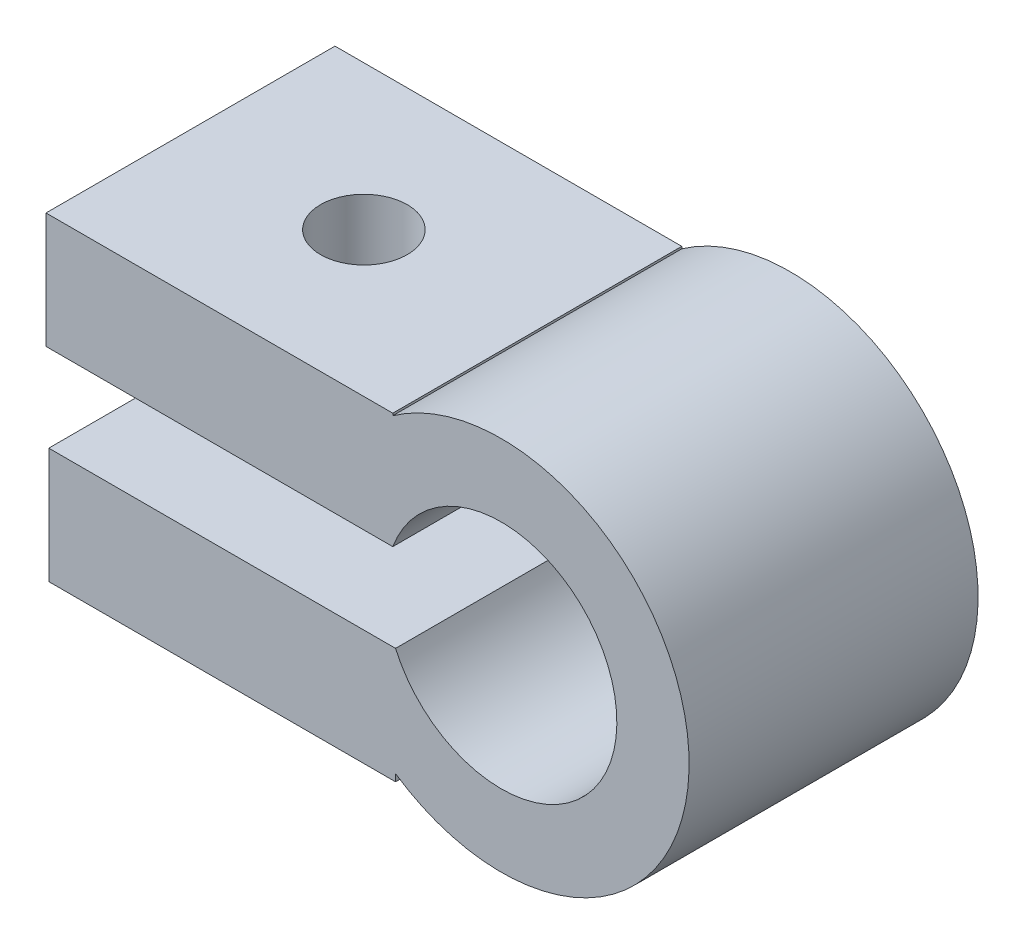
SolidWorks part; units mm, degrees
ref_plane "Front Plane" through (0, 0, 0) normal (0, 0, 1) x (1, 0, 0)
ref_plane "Top Plane" through (0, 0, 0) normal (0, 1, 0) x (1, 0, 0)
ref_plane "Right Plane" through (0, 0, 0) normal (1, 0, 0) x (0, 0, -1)
sketch "Sketch1" plane through (0, 0, 0) normal (0, 0, 1) x (1, 0, 0)
  circle A0 centre (-12.3154, 2.5507) radius 4
  circle A1 centre (-12.3154, 2.5507) radius 6.5
  dimension "D1" = 8
  dimension "D2" = 13
extrude "Boss-Extrude1" add sketch "Sketch1" along normal blind 10 contours A1
sketch "Sketch2" plane through (0, 0, 10) normal (0, 0, 1) x (1, 0, 0)
  line L1 (-18.9664, 3.9327) -> (-15.7482, 3.9327)
  line L2 (-18.9664, 3.9327) -> (-18.9664, 0.9327)
  line L3 (-18.9664, 0.9327) -> (-15.7482, 0.9327)
  line L4 (-15.7482, 3.9327) -> (-15.7482, 0.9327)
  dimension "D1" = 3
extrude "Cut-Extrude1" cut sketch "Sketch2" against normal blind 33
sketch "Sketch3" plane through (0, 0, 10) normal (0, 0, 1) x (1, 0, 0)
  line L0 (-15.9736, 0.9327) -> (-27.9736, 0.9327)
  line L1 (-16.0691, 7.9327) -> (-28.0691, 7.9327)
  line L2 (-16.0691, 7.9327) -> (-16.0691, 3.9327)
  line L3 (-16.0691, 3.9327) -> (-28.0691, 3.9327)
  line L4 (-28.0691, 7.9327) -> (-28.0691, 3.9327)
  line L5 (-15.9736, 0.9327) -> (-15.9736, -3.0673)
  line L6 (-15.9736, -3.0673) -> (-27.9736, -3.0673)
  line L7 (-27.9736, 0.9327) -> (-27.9736, -3.0673)
  line L8 (-16.0691, 3.9327) -> (-18.6668, 3.9327) construction
  line L9 (-18.6108, 0.9327) -> (-15.9736, 0.9327) construction
  dimension "D1" = 12
  dimension "D2" = 0
  dimension "D3" = 0
  dimension "D4" = 0
  dimension "D5" = 0
  dimension "D6" = 12
  dimension "D7" = 4
  dimension "D8" = 4
extrude "Boss-Extrude2" add sketch "Sketch3" against normal blind 10 contours L2 L1 L4 L3 | L0 L7 L6 L5
sketch "Sketch4" plane through (0, 7.9327, 0) normal (0, 1, 0) x (1, 0, 0)
  line L0 (-16.0691, 0) -> (-28.0691, 0) construction
  line L1 (-28.0691, 0) -> (-28.0691, -10) construction
  circle A0 centre (-22.0691, -5) radius 1.5
  dimension "D1" = 5
  dimension "D2" = 6
  dimension "D3" = 3
extrude "Cut-Extrude2" cut sketch "Sketch4" against normal blind 40
sketch "Sketch5" plane through (0, -3.0673, 0) normal (0, -1, 0) x (-1, 0, 0)
  line L1 (19.0511, -6.6695) -> (22.0511, -8.4015)
  line L2 (22.0511, -8.4015) -> (25.0511, -6.6695)
  line L3 (25.0511, -6.6695) -> (25.0511, -3.2054)
  line L4 (25.0511, -3.2054) -> (22.0511, -1.4733)
  line L5 (22.0511, -1.4733) -> (19.0511, -3.2054)
  line L6 (19.0511, -3.2054) -> (19.0511, -6.6695)
  circle A0 centre (22.0511, -4.9374) radius 3 construction
  dimension "D1" = 6
extrude "Cut-Extrude3" cut sketch "Sketch5" against normal blind 3
